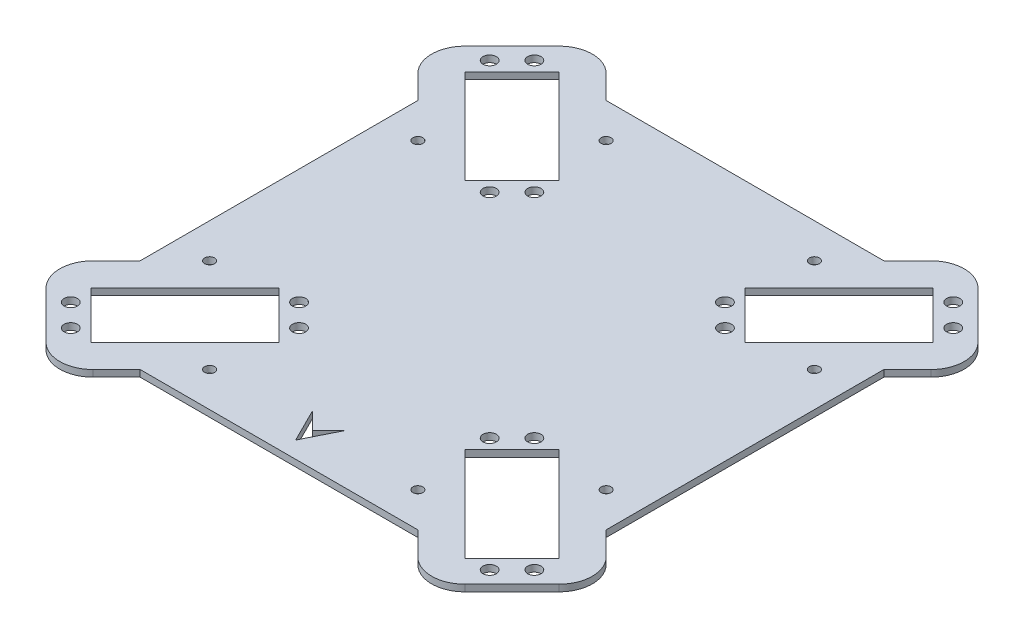
SolidWorks part; units mm, degrees
ref_plane "Front Plane" through (0, 0, 0) normal (0, 0, 1) x (1, 0, 0)
ref_plane "Top Plane" through (0, 0, 0) normal (0, 1, 0) x (1, 0, 0)
ref_plane "Right Plane" through (0, 0, 0) normal (1, 0, 0) x (0, 0, -1)
sketch "Sketch1" plane through (0, 0, 0) normal (0, 1, 0) x (1, 0, 0)
  line L1 (0, 0) -> (140, 0)
  line L2 (0, 0) -> (0, 140)
  line L3 (0, 140) -> (140, 140)
  line L4 (140, 0) -> (140, 140)
  dimension "D1" = 140
  dimension "D2" = 140
extrude "Boss-Extrude1" add sketch "Sketch1" along normal blind 2
sketch "Sketch2" plane through (0, 2, 0) normal (0, 1, 0) x (1, 0, 0)
  line L0 (70, 140) -> (70, 0) construction
  line L1 (140, 140) -> (0, 140) construction
  line L2 (0, 0) -> (140, 0) construction
  line L3 (140, 70) -> (0, 70) construction
  line L4 (140, 0) -> (140, 140) construction
  line L5 (0, 140) -> (0, 0) construction
  line L6 (70, 70) -> (140, 140) construction
  line L7 (125.8579, 125.8579) -> (140, 111.7157) construction
  line L8 (125.8579, 125.8579) -> (111.7157, 140) construction
  line L9 (111.7157, 140) -> (140, 111.7157)
  line L10 (111.7157, 140) -> (125.8579, 154.1421)
  line L11 (140, 111.7157) -> (154.1421, 125.8579)
  line L12 (125.8579, 154.1421) -> (154.1421, 125.8579)
  line L13 (0, 111.7157) -> (-14.1421, 125.8579)
  line L14 (14.1421, 154.1421) -> (-14.1421, 125.8579)
  line L15 (28.2843, 140) -> (14.1421, 154.1421)
  line L16 (28.2843, 140) -> (0, 111.7157)
  line L17 (28.2843, 0) -> (0, 28.2843)
  line L18 (28.2843, 0) -> (14.1421, -14.1421)
  line L19 (14.1421, -14.1421) -> (-14.1421, 14.1421)
  line L20 (0, 28.2843) -> (-14.1421, 14.1421)
  line L21 (140, 28.2843) -> (154.1421, 14.1421)
  line L22 (125.8579, -14.1421) -> (154.1421, 14.1421)
  line L23 (111.7157, 0) -> (125.8579, -14.1421)
  line L24 (111.7157, 0) -> (140, 28.2843)
  point P33 (140, 111.7157)
  point P34 (111.7157, 140)
  dimension "D1" = 40
  dimension "D2" = 20
extrude "Boss-Extrude3" add sketch "Sketch2" against normal blind 2
sketch "Sketch3" plane through (0, 2, 0) normal (0, 1, 0) x (1, 0, 0)
  line L0 (0, 0) -> (140, 140) construction
  line L1 (-14.1421, 14.1421) -> (14.1421, -14.1421) construction
  line L2 (154.1421, 125.8579) -> (125.8579, 154.1421) construction
  line L3 (0, 28.2843) -> (28.2843, 0) construction
  line L4 (6.7246, 6.7246) -> (20.8667, -7.4176) construction
  line L5 (14.1421, -14.1421) -> (28.2843, 0) construction
  line L6 (35.0089, 35.0089) -> (47.7718, 22.2459) construction
  line L7 (13.7957, -0.3465) -> (42.0799, 27.9378)
  line L8 (13.7957, -0.3465) -> (-0.3465, 13.7957)
  line L9 (42.0799, 27.9378) -> (27.9378, 42.0799)
  line L10 (-0.3465, 13.7957) -> (27.9378, 42.0799)
  line L11 (3.7194, 3.7194) -> (10.7828, -3.344) construction
  line L12 (27.9378, 13.7957) -> (13.7957, 27.9378) construction
  line L13 (0, 70) -> (140, 70) construction
  line L14 (0, 111.7157) -> (0, 28.2843) construction
  line L15 (140, 28.2843) -> (140, 111.7157) construction
  line L16 (70, 0) -> (70, 140) construction
  line L17 (28.2843, 0) -> (111.7157, 0) construction
  line L18 (111.7157, 140) -> (28.2843, 140) construction
  line L19 (97.9201, 27.9378) -> (112.0622, 42.0799)
  line L20 (140.3465, 13.7957) -> (112.0622, 42.0799)
  line L21 (126.2043, -0.3465) -> (140.3465, 13.7957)
  line L22 (126.2043, -0.3465) -> (97.9201, 27.9378)
  line L23 (126.2043, 140.3465) -> (97.9201, 112.0622)
  line L24 (126.2043, 140.3465) -> (140.3465, 126.2043)
  line L25 (140.3465, 126.2043) -> (112.0622, 97.9201)
  line L26 (97.9201, 112.0622) -> (112.0622, 97.9201)
  line L27 (42.0799, 112.0622) -> (27.9378, 97.9201)
  line L28 (-0.3465, 126.2043) -> (27.9378, 97.9201)
  line L29 (13.7957, 140.3465) -> (-0.3465, 126.2043)
  line L30 (13.7957, 140.3465) -> (42.0799, 112.0622)
  circle A0 centre (7.0781, 0.3606) radius 2
  circle A1 centre (0.3606, 7.0781) radius 2
  circle A2 centre (41.3728, 34.6553) radius 2
  circle A3 centre (34.6553, 41.3728) radius 2
  circle A4 centre (132.9219, 0.3606) radius 2
  circle A5 centre (139.6394, 7.0781) radius 2
  circle A6 centre (98.6272, 34.6553) radius 2
  circle A7 centre (105.3447, 41.3728) radius 2
  circle A8 centre (132.9219, 139.6394) radius 2
  circle A9 centre (139.6394, 132.9219) radius 2
  circle A10 centre (98.6272, 105.3447) radius 2
  circle A11 centre (105.3447, 98.6272) radius 2
  circle A12 centre (7.0781, 139.6394) radius 2
  circle A13 centre (0.3606, 132.9219) radius 2
  circle A14 centre (41.3728, 105.3447) radius 2
  circle A15 centre (34.6553, 98.6272) radius 2
  point P10 (14.1421, 14.1421)
  point P11 (35.0089, 35.0089)
  point P13 (6.7246, 6.7246)
  dimension "D5" = 4
  dimension "D6" = 9.5
  dimension "D7" = 4.25
  dimension "D1" = 29.51
  dimension "D2" = 10.49
  dimension "D3" = 20
  dimension "D4" = 4.25
extrude "Cut-Extrude1" cut sketch "Sketch3" against normal blind 2
fillet "Fillet1" radius 10 8 edges at (154.1421, 1, -14.1421) (125.8579, 1, 14.1421) (14.1421, 1, 14.1421) (-14.1421, 1, -14.1421) (-14.1421, 1, -125.8579) (14.1421, 1, -154.1421) (125.8579, 1, -154.1421) (154.1421, 1, -125.8579)
sketch "Sketch4" plane through (0, 2, 0) normal (0, 1, 0) x (1, 0, 0)
  line L0 (70, 140) -> (70, 0) construction
  line L1 (111.7157, 140) -> (28.2843, 140) construction
  line L2 (28.2843, 0) -> (111.7157, 0) construction
  line L3 (0, 70) -> (140, 70) construction
  line L4 (0, 111.7157) -> (0, 28.2843) construction
  line L5 (140, 28.2843) -> (140, 111.7157) construction
  line L6 (28.2843, 0) -> (70, 41.7157) construction
  line L7 (35.0089, 35.0089) -> (6.7246, 6.7246) construction
  line L8 (42.0799, 27.9378) -> (27.9378, 42.0799) construction
  line L9 (-0.3465, 13.7957) -> (13.7957, -0.3465) construction
  line L10 (42.0799, 27.9378) -> (28.2843, 0) construction
  line L11 (35.1821, 13.9689) -> (38.7176, 10.4334) construction
  circle A0 centre (38.7176, 10.4334) radius 1.5
  circle A1 centre (10.4334, 38.7176) radius 1.5
  circle A2 centre (101.2824, 10.4334) radius 1.5
  circle A3 centre (129.5666, 38.7176) radius 1.5
  circle A4 centre (38.7176, 129.5666) radius 1.5
  circle A5 centre (10.4334, 101.2824) radius 1.5
  circle A6 centre (101.2824, 129.5666) radius 1.5
  circle A7 centre (129.5666, 101.2824) radius 1.5
  dimension "D1" = 3
extrude "Cut-Extrude2" cut sketch "Sketch4" against normal blind 2
sketch "Sketch5" plane through (0, 2, 0) normal (0, 1, 0) x (1, 0, 0)
  line L0 (70, 0) -> (70, 140) construction
  line L1 (28.2843, 0) -> (111.7157, 0) construction
  line L2 (111.7157, 140) -> (28.2843, 140) construction
  line L3 (70, 15) -> (75, 15) construction
  line L4 (75, 15) -> (70, 10)
  line L5 (75, 15) -> (70, 5)
  line L6 (65, 15) -> (70, 5)
  line L7 (65, 15) -> (70, 10)
  dimension "D1" = 5
  dimension "D2" = 5
  dimension "D3" = 10
  dimension "D4" = 5
extrude "Cut-Extrude3" cut sketch "Sketch5" against normal blind 2
